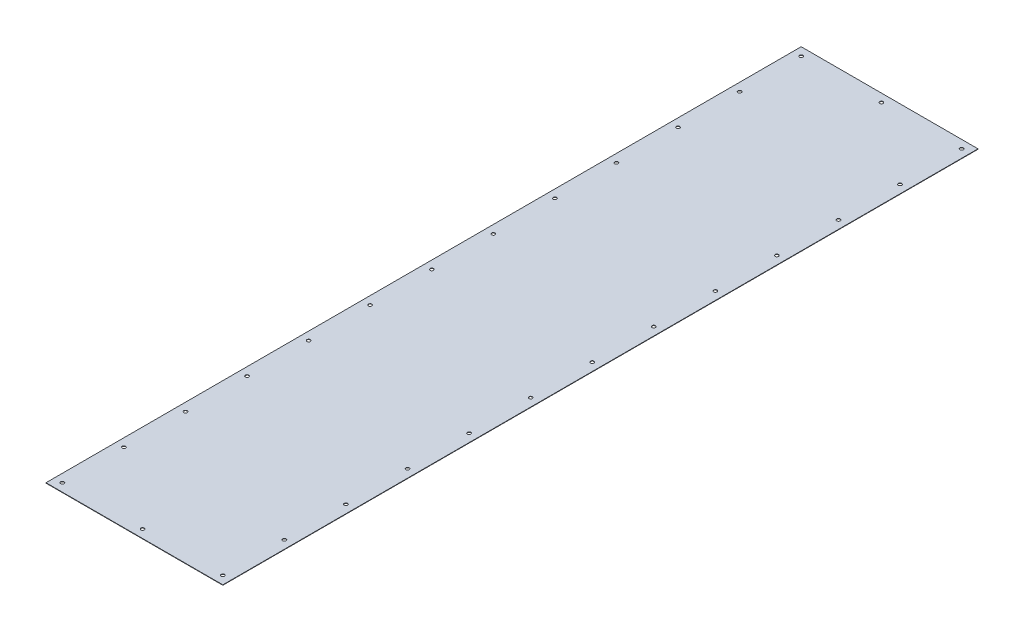
SolidWorks part; units mm, degrees
ref_plane "Front Plane" through (0, 0, 0) normal (0, 0, 1) x (1, 0, 0)
ref_plane "Top Plane" through (0, 0, 0) normal (0, 1, 0) x (1, 0, 0)
ref_plane "Right Plane" through (0, 0, 0) normal (1, 0, 0) x (0, 0, -1)
sketch "Sketch1" plane through (0, 0, 0) normal (0, 1, 0) x (1, 0, 0)
  line L1 (-215.425, 920) -> (215.425, 920)
  line L2 (-215.425, 920) -> (-215.425, -920)
  line L3 (-215.425, -920) -> (215.425, -920)
  line L4 (215.425, 920) -> (215.425, -920)
  line L5 (-215.425, 920) -> (215.425, -920) construction
  line L6 (-215.425, -920) -> (215.425, 920) construction
  line L7 (-195.425, -900) -> (195.425, -900) construction
  line L8 (-195.425, -900) -> (-195.425, 900) construction
  line L9 (-195.425, 900) -> (195.425, 900) construction
  line L10 (195.425, -900) -> (195.425, 900) construction
  line L11 (-195.425, -900) -> (195.425, 900) construction
  line L12 (-195.425, 900) -> (195.425, -900) construction
  circle A0 centre (-195.425, 900) radius 4.1
  circle A1 centre (195.425, 900) radius 4.1
  circle A2 centre (-195.425, 750) radius 4.1
  circle A3 centre (195.425, 750) radius 4.1
  circle A4 centre (-195.425, 600) radius 4.1
  circle A5 centre (195.425, 600) radius 4.1
  circle A6 centre (-195.425, 450) radius 4.1
  circle A7 centre (195.425, 450) radius 4.1
  circle A8 centre (-195.425, 300) radius 4.1
  circle A9 centre (195.425, 300) radius 4.1
  circle A10 centre (-195.425, 150) radius 4.1
  circle A11 centre (195.425, 150) radius 4.1
  circle A12 centre (-195.425, 0) radius 4.1
  circle A13 centre (195.425, 0) radius 4.1
  circle A14 centre (-195.425, -150) radius 4.1
  circle A15 centre (195.425, -150) radius 4.1
  circle A16 centre (-195.425, -300) radius 4.1
  circle A17 centre (195.425, -300) radius 4.1
  circle A18 centre (-195.425, -450) radius 4.1
  circle A19 centre (195.425, -450) radius 4.1
  circle A20 centre (-195.425, -600) radius 4.1
  circle A21 centre (195.425, -600) radius 4.1
  circle A22 centre (-195.425, -750) radius 4.1
  circle A23 centre (195.425, -750) radius 4.1
  circle A24 centre (-195.425, -900) radius 4.1
  circle A25 centre (195.425, -900) radius 4.1
  circle A26 centre (0, -900) radius 4.1
  circle A27 centre (0, 900) radius 4.1
  point P0 (0, 0)
  point P6 (0, 0)
  dimension "D5" = 8.2
  dimension "D7" = 8.2
  dimension "D8" = 8.2
  dimension "D1" = 1840
  dimension "D2" = 390.85
  dimension "D3" = 20
  dimension "D4" = 20
  dimension "D9" = 150
  dimension "D6" = 13
extrude "Boss-Extrude1" add sketch "Sketch1" along normal blind 1
